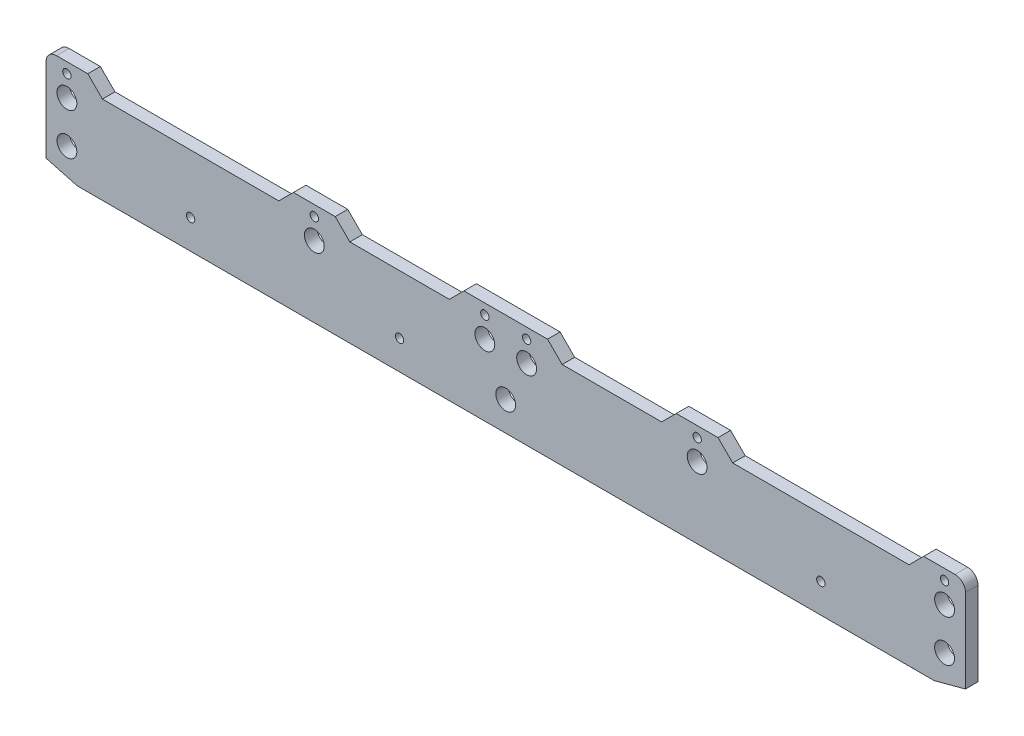
SolidWorks part; units mm, degrees
ref_plane "Alzado" through (0, 0, 0) normal (0, 0, 1) x (1, 0, 0)
ref_plane "Planta" through (0, 0, 0) normal (0, 1, 0) x (1, 0, 0)
ref_plane "Vista lateral" through (0, 0, 0) normal (1, 0, 0) x (0, 0, -1)
sketch "Croquis1" plane through (0, 0, 0) normal (0, 0, 1) x (1, 0, 0)
  line L0 (-220, 0) -> (220, 0)
  line L1 (-220, 0) -> (-220, 38)
  line L2 (-220, 38) -> (-108.6, 38)
  line L3 (-108.6, 38) -> (-101.6, 45)
  line L4 (-101.6, 45) -> (-81.6, 45)
  line L5 (-81.6, 45) -> (-74.6, 38)
  line L6 (-74.6, 38) -> (-27, 38)
  line L7 (-27, 38) -> (-20, 45)
  line L8 (-20, 45) -> (20, 45)
  line L9 (-220, 10) -> (220, 10) construction
  line L10 (0, 45) -> (0, 2.472) construction
  line L11 (-220, 20) -> (220, 20) construction
  line L12 (27, 38) -> (20, 45)
  line L13 (74.6, 38) -> (27, 38)
  line L14 (81.6, 45) -> (74.6, 38)
  line L15 (101.6, 45) -> (81.6, 45)
  line L16 (108.6, 38) -> (101.6, 45)
  line L17 (220, 38) -> (108.6, 38)
  line L18 (220, 0) -> (220, 38)
  line L19 (-210, 38) -> (-210, 0) construction
  line L20 (-91.6, 45) -> (-91.6, 0) construction
  line L21 (-210, 30) -> (-91.6, 30) construction
  line L22 (-10, 45) -> (-10, 0) construction
  line L23 (-91.6, 30) -> (-10, 30) construction
  circle A0 centre (-210, 10) radius 4.75
  circle A1 centre (-210, 30) radius 4.75
  circle A2 centre (210, 10) radius 4.75
  circle A3 centre (210, 30) radius 4.75
  circle A4 centre (-91.6, 30) radius 4.75
  circle A5 centre (-10, 30) radius 4.75
  circle A6 centre (10, 30) radius 4.75
  circle A7 centre (91.6, 30) radius 4.75
  circle A8 centre (0, 10) radius 4.75
  point P4 (0, 0)
  dimension "D6" = 9.5
  dimension "D1" = 440
  dimension "D2" = 38
  dimension "D3" = 10
  dimension "D4" = 20
  dimension "D5" = 10
  dimension "D7" = 10
  dimension "D8" = 118.4
  dimension "D9" = 135
  dimension "D10" = 45
  dimension "D11" = 20
  dimension "D12" = 40
  dimension "D13" = 135
  dimension "D14" = 10
extrude "Saliente-Extruir1" add sketch "Croquis1" along normal blind 6
sketch "Croquis2" plane through (0, 0, 6) normal (0, 0, 1) x (1, 0, 0)
  line L0 (0, 45) -> (0, 0) construction
  line L1 (20, 45) -> (-20, 45) construction
  line L2 (-220, 38) -> (-220, 45)
  line L3 (-220, 45) -> (-200, 45)
  line L4 (-200, 45) -> (-193, 38)
  line L5 (-108.6, 38) -> (-220, 38) construction
  line L6 (-193, 38) -> (-220, 38)
  line L7 (-81.6, 45) -> (-101.6, 45) construction
  line L8 (200, 45) -> (193, 38)
  line L9 (220, 45) -> (200, 45)
  line L10 (220, 38) -> (220, 45)
  line L11 (193, 38) -> (220, 38)
  dimension "D1" = 135
  dimension "D2" = 20
extrude "Saliente-Extruir2" add sketch "Croquis2" against normal up to surface (6 mm away) up to face at (0, 35.875, 0)
sketch "Croquis3" plane through (0, 0, 6) normal (0, 0, 1) x (1, 0, 0)
  line L0 (0, 45) -> (0, 0) construction
  line L1 (20, 45) -> (-20, 45) construction
  line L2 (0, 40) -> (-220, 40) construction
  line L3 (-220, 45) -> (-220, 0) construction
  line L4 (-91.6, 45) -> (-91.6, 0) construction
  line L5 (-81.6, 45) -> (-101.6, 45) construction
  line L6 (-220, 0) -> (220, 0) construction
  line L7 (-210, 30) -> (-210, 40) construction
  line L8 (-10, 30) -> (-10, 40) construction
  line L9 (-210, 10) -> (0, 10) construction
  line L10 (-150.8, 38) -> (-150.8, 10) construction
  line L11 (-108.6, 38) -> (-193, 38) construction
  line L12 (-50.8, 38) -> (-50.8, 10) construction
  line L13 (-27, 38) -> (-74.6, 38) construction
  circle A0 centre (-91.6, 40) radius 2
  circle A1 centre (-210, 40) radius 2
  circle A2 centre (-10, 40) radius 2
  circle A3 centre (10, 40) radius 2
  circle A4 centre (91.6, 40) radius 2
  circle A5 centre (210, 40) radius 2
  circle A6 centre (-150.8, 10) radius 2
  circle A7 centre (-50.8, 10) radius 2
  circle A8 centre (150.8, 10) radius 2
  dimension "D2" = 4
  dimension "D1" = 5
extrude "Cortar-Extruir1" cut sketch "Croquis3" against normal through all
sketch "Croquis4" plane through (0, 0, 6) normal (0, 0, 1) x (1, 0, 0)
  line L0 (220, 0) -> (-220, 0)
  line L1 (-220, 0) -> (-205.0718, -4)
  line L2 (-205.0718, -4) -> (205.0718, -4)
  line L3 (0, 0) -> (0, -4) construction
  line L4 (220, 0) -> (205.0718, -4)
  dimension "D1" = 15
  dimension "D2" = 4
extrude "Saliente-Extruir3" add sketch "Croquis4" against normal up to surface (6 mm away) up to face at (-208, 40, 0)
fillet "Redondeo3" radius 5 2 edges at (220, 45, 3) (-220, 45, 3)
